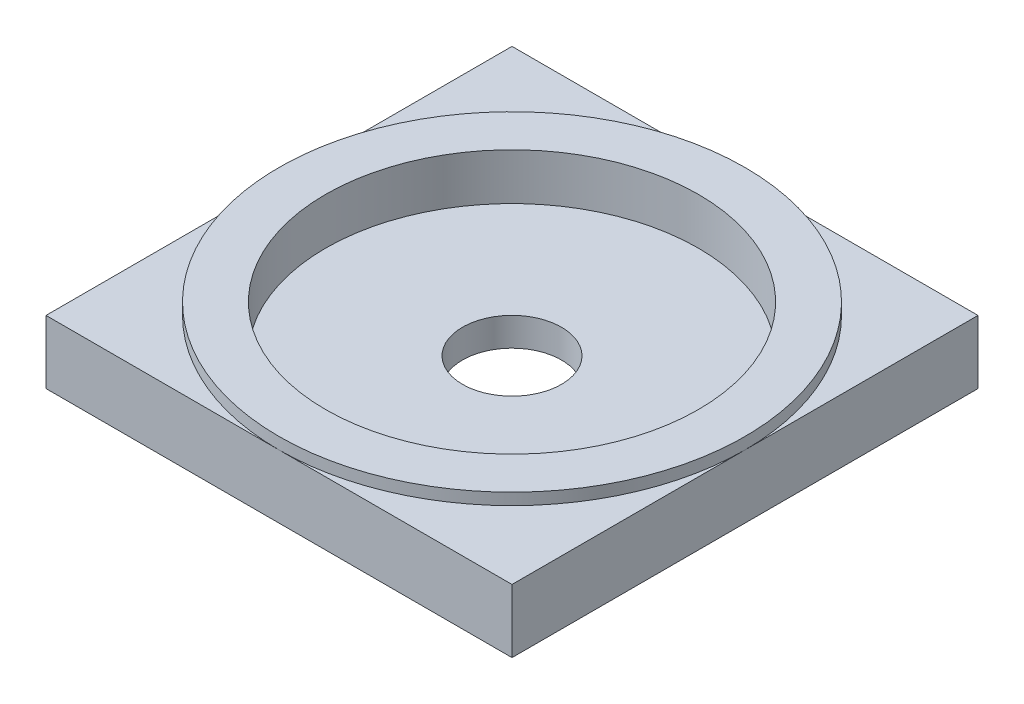
SolidWorks part; units mm, degrees
material "Alloy Steel"
ref_plane "Front Plane" through (0, 0, 0) normal (0, 0, 1) x (1, 0, 0)
ref_plane "Top Plane" through (0, 0, 0) normal (0, 1, 0) x (1, 0, 0)
ref_plane "Right Plane" through (0, 0, 0) normal (1, 0, 0) x (0, 0, -1)
sketch "Sketch2" plane through (0, 0, 0) normal (0, 1, 0) x (1, 0, 0)
  line L1 (-31.75, 31.75) -> (31.75, 31.75)
  line L2 (-31.75, 31.75) -> (-31.75, -31.75)
  line L3 (-31.75, -31.75) -> (31.75, -31.75)
  line L4 (31.75, 31.75) -> (31.75, -31.75)
  line L5 (-31.75, 31.75) -> (31.75, -31.75) construction
  line L6 (-31.75, -31.75) -> (31.75, 31.75) construction
  circle A0 centre (0, 0) radius 31.75 construction
  dimension "D1" = 63.5
extrude "Boss-Extrude1" add sketch "Sketch2" against normal blind 8.636
sketch "Sketch3" plane through (0, 0, 0) normal (0, 1, 0) x (1, 0, 0)
  circle A0 centre (0, 0) radius 31.75
  dimension "D1" = 63.5
extrude "Boss-Extrude2" add sketch "Sketch3" along normal blind 1.5875
sketch "Sketch4" plane through (0, 1.5875, 0) normal (0, 1, 0) x (1, 0, 0)
  circle A0 centre (0, 0) radius 25.4
  dimension "D1" = 50.8
extrude "Cut-Extrude1" cut sketch "Sketch4" against normal blind 6.35
sketch "Sketch5" plane through (0, -4.7625, 0) normal (0, 1, 0) x (1, 0, 0)
  circle A0 centre (0, 0) radius 6.7462
  circle A1 centre (0, 0) radius 6.7462 construction
extrude "Cut-Extrude3" cut sketch "Sketch5" against normal through all
